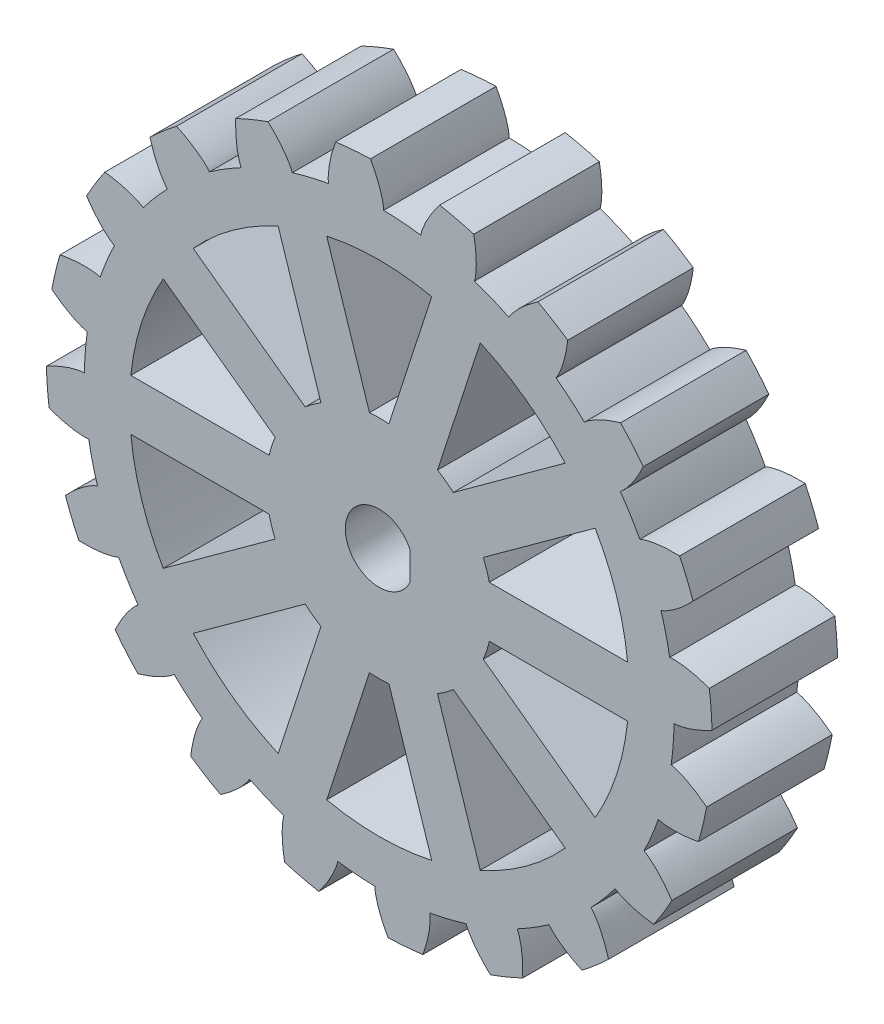
SolidWorks part; units mm, degrees
ref_plane "Front Plane" through (0, 0, 0) normal (0, 0, 1) x (1, 0, 0)
ref_plane "Top Plane" through (0, 0, 0) normal (0, 1, 0) x (1, 0, 0)
ref_plane "Right Plane" through (0, 0, 0) normal (1, 0, 0) x (0, 0, -1)
sketch "Sketch6" plane through (0, 0, 0) normal (0, 0, 1) x (1, 0, 0)
  line L0 (87.6899, 36.827) -> (87.6899, 90.4407) construction
  line L1 (87.6899, 61.8261) -> (62.7181, 61.8261) construction
  line L2 (87.6899, 61.8261) -> (56.3004, 50.4013) construction
  line L3 (79.6554, 58.9018) -> (87.6899, 61.8261) construction
  line L4 (77.8074, 58.1386) -> (87.3788, 62.5771) construction
  line L5 (76.0304, 57.2208) -> (86.9259, 63.45) construction
  line L6 (74.338, 56.1551) -> (86.3097, 64.4252) construction
  line L7 (81.5622, 59.5052) -> (87.8859, 61.2139) construction
  line L8 (83.5134, 59.9442) -> (87.9914, 60.7533) construction
  line L9 (85.4949, 60.2157) -> (88.0342, 60.454) construction
  line L10 (87.4923, 60.3177) -> (88.0428, 60.3223) construction
  line L11 (88.0428, 60.3223) -> (88.0425, 60.3158) construction
  line L12 (88.0425, 60.3158) -> (88.0425, 60.3094) construction
  line L13 (87.6899, 36.827) -> (85.2614, 67.5128) construction
  line L14 (111.173, 36.827) -> (112.6899, 36.827) construction
  line L15 (112.6899, 36.827) -> (114.2068, 36.827) construction
  circle A0 centre (87.6899, 36.827) radius 26.5169 construction
  circle A1 centre (87.6899, 36.827) radius 25 construction
  circle A2 centre (87.6899, 36.827) radius 23.4915 construction
  arc A3 (79.6554, 58.9018) -> (77.8074, 58.1386) centre (87.6899, 36.827) ccw construction
  arc A4 (77.8074, 58.1386) -> (76.0304, 57.2208) centre (87.6899, 36.827) ccw construction
  arc A5 (76.0304, 57.2208) -> (74.338, 56.1551) centre (87.6899, 36.827) ccw construction
  arc A6 (79.6554, 58.9018) -> (81.5622, 59.5052) centre (87.6899, 36.827) cw construction
  arc A7 (81.5622, 59.5052) -> (83.5134, 59.9442) centre (87.6899, 36.827) cw construction
  arc A8 (83.5134, 59.9442) -> (85.4949, 60.2157) centre (87.6899, 36.827) cw construction
  arc A9 (85.4949, 60.2157) -> (87.4923, 60.3177) centre (87.6899, 36.827) cw construction
  circle A10 centre (87.6899, 36.827) radius 23.485 construction
  spline S0 degree 3 poles (88.0425, 60.3094) (88.0393, 60.4586) (87.9965, 60.763) (87.8787, 61.2705) (87.6796, 61.8825) (87.2187, 62.9893) (86.7132, 63.8389) (86.3097, 64.4252) knots 0 0 0 0 0.099096 0.20382 0.346132 0.526411 1 1 1 1 construction
  spline S1 degree 3 poles (83.648, 59.9616) (83.6277, 60.1095) (83.6221, 60.4168) (83.6586, 60.9366) (83.759, 61.5723) (84.04, 62.7378) (84.4056, 63.6562) (84.7119, 64.2988) knots 0 0 0 0 0.099096 0.20382 0.346132 0.526411 1 1 1 1 construction
  point P7 (79.6554, 58.9018)
  dimension "D2" = 50
  dimension "D4" = 2
  dimension "D7" = 2
  dimension "D13" = 2
  dimension "D17" = 2
  dimension "D3" = 20
  dimension "D5" = 8.5502
  dimension "D6" = 10.5505
  dimension "D8" = 12.5505
  dimension "D9" = 2
  dimension "D10" = 14.5505
  dimension "D11" = 2
  dimension "D12" = 6.5505
  dimension "D14" = 4.5505
  dimension "D15" = 2
  dimension "D16" = 2.5505
  dimension "D18" = 0.5505
  dimension "D19" = 4.525
sketch "Sketch7" plane through (0, 0, 0) normal (0, 0, 1) x (1, 0, 0)
  circle A0 centre (87.6899, 36.827) radius 23.485 construction
  circle A1 centre (87.6899, 36.827) radius 26.5169 construction
  arc A2 (88.0425, 60.3094) -> (83.648, 59.9616) centre (87.6899, 36.827) ccw construction
  arc A3 (86.9912, 63.3347) -> (84.2104, 63.1146) centre (87.6899, 36.827) ccw construction
  spline S0 degree 3 poles (-1911.6865, 35.1483) (71.5756, 40.4372) (89.8382, 52.8293) (87.8787, 61.2705) (87.6796, 61.8825) (75.5402, 91.0375) (-65.3864, 59.6539) (2084.1552, 156.0334) knots -5.410264 -5.410264 -5.410264 -5.410264 0.099096 0.20382 0.346132 0.526411 21.176223 21.176223 21.176223 21.176223 only from (88.0425, 60.3094) to (86.3097, 64.4252) construction
  spline S1 degree 3 poles (2062.4411, 349.6638) (103.0357, 42.927) (83.0512, 52.2922) (83.6586, 60.9366) (83.759, 61.5723) (91.1612, 92.2738) (235.27, 83.4481) (-1902.673, -159.4872) knots -5.410264 -5.410264 -5.410264 -5.410264 0.099096 0.20382 0.346132 0.526411 21.176223 21.176223 21.176223 21.176223 only from (83.648, 59.9616) to (84.7119, 64.2988) construction
  spline S2 degree 3 poles (88.0425, 60.3094) (88.0393, 60.4586) (87.9965, 60.763) (87.8787, 61.2705) (87.6796, 61.8825) (87.3837, 62.5931) (87.1297, 63.087) (86.9912, 63.3347) knots 0 0 0 0 0.099096 0.20382 0.346132 0.526411 0.715001 0.715001 0.715001 0.715001 construction
  spline S3 degree 3 poles (83.648, 59.9616) (83.6277, 60.1095) (83.6221, 60.4168) (83.6586, 60.9366) (83.759, 61.5723) (83.9394, 62.3206) (84.1125, 62.8482) (84.2104, 63.1146) knots 0 0 0 0 0.099096 0.20382 0.346132 0.526411 0.715001 0.715001 0.715001 0.715001 construction
sketch "Sketch11" plane through (0, 0, 0) normal (0, 0, 1) x (1, 0, 0)
  circle A0 centre (0, 0) radius 23.485
  dimension "D1" = 46.97
extrude "Boss-Extrude6" add sketch "Sketch11" along normal blind 10
sketch "Sketch12" plane through (0, 0, 10) normal (0, 0, 1) x (1, 0, 0)
  arc A2 (-0.6987, 26.5077) -> (-3.4795, 26.2876) centre (0, 0) ccw
  arc A3 (0.3526, 23.4824) -> (-4.0419, 23.1346) centre (0, 0) ccw
  spline S2 degree 3 poles (-4.0419, 23.1346) (-4.0622, 23.2824) (-4.0678, 23.5897) (-4.0313, 24.1095) (-3.9309, 24.7452) (-3.7505, 25.4935) (-3.5774, 26.0212) (-3.4795, 26.2876) knots 0 0 0 0 0.099096 0.20382 0.346132 0.526411 0.715001 0.715001 0.715001 0.715001
  spline S3 degree 3 poles (0.3526, 23.4824) (0.3494, 23.6316) (0.3066, 23.9359) (0.1887, 24.4435) (-0.0104, 25.0555) (-0.3062, 25.7661) (-0.5602, 26.26) (-0.6987, 26.5077) knots 0 0 0 0 0.099096 0.20382 0.346132 0.526411 0.715001 0.715001 0.715001 0.715001
extrude "Boss-Extrude7" add sketch "Sketch12" against normal blind 10
pattern_circular "CirPattern2" count 20 over 360 of "Boss-Extrude7"
sketch "Sketch13" plane through (0, 0, 10) normal (0, 0, 1) x (1, 0, 0)
  line L0 (2.45, 1.1347) -> (2.45, -1.1347)
  arc A0 (2.45, 1.1347) -> (2.45, -1.1347) centre (0, 0) ccw
  dimension "D1" = 2.7
  dimension "D2" = 2.45
extrude "Cut-Extrude2" cut sketch "Sketch13" against normal blind 10
sketch "Sketch14" plane through (0, 0, 0) normal (0, 0, -1) x (-1, 0, 0)
  line L1 (-7.3601, 2.8365) -> (-17.1995, 9.9851)
  line L2 (-7.6217, -2.0314) -> (-19.7838, -2.0314)
  line L4 (-7.6217, 2.0314) -> (-19.7838, 2.0314)
  line L8 (-4.972, 6.1234) -> (-14.8114, 13.2721)
  line L9 (-4.2873, 6.6209) -> (-8.0455, 18.1877)
  line L10 (-0.4232, 7.8764) -> (-4.1815, 19.4432)
  line L11 (0.4232, 7.8764) -> (4.1815, 19.4432)
  line L12 (4.2873, 6.6209) -> (8.0455, 18.1877)
  line L13 (4.972, 6.1234) -> (14.8114, 13.2721)
  line L14 (7.3601, 2.8365) -> (17.1995, 9.9851)
  line L15 (7.6217, 2.0314) -> (19.7838, 2.0314)
  line L16 (7.6217, -2.0314) -> (19.7838, -2.0314)
  line L17 (7.3601, -2.8365) -> (17.1995, -9.9851)
  line L18 (4.972, -6.1234) -> (14.8114, -13.2721)
  line L19 (4.2873, -6.6209) -> (8.0455, -18.1877)
  line L20 (0.4232, -7.8764) -> (4.1815, -19.4432)
  line L21 (-0.4232, -7.8764) -> (-4.1815, -19.4432)
  line L22 (-4.2873, -6.6209) -> (-8.0455, -18.1877)
  line L23 (-4.972, -6.1234) -> (-14.8114, -13.2721)
  line L24 (-7.3601, -2.8365) -> (-17.1995, -9.9851)
  circle A0 centre (0, 0) radius 19.8878 construction
  arc A1 (-4.1815, -19.4432) -> (4.1815, -19.4432) centre (0, 0) ccw
  circle A2 centre (0, 0) radius 22.8878 construction
  arc A3 (-0.4232, -7.8764) -> (0.4232, -7.8764) centre (0, 0) ccw
  circle A4 centre (0, 0) radius 7.8878 construction
  arc A5 (-4.972, -6.1234) -> (-4.2873, -6.6209) centre (0, 0) ccw
  arc A6 (-14.8114, -13.2721) -> (-8.0455, -18.1877) centre (0, 0) ccw
  arc A7 (4.2873, -6.6209) -> (4.972, -6.1234) centre (0, 0) ccw
  arc A8 (8.0455, -18.1877) -> (14.8114, -13.2721) centre (0, 0) ccw
  arc A9 (17.1995, -9.9851) -> (19.7838, -2.0314) centre (0, 0) ccw
  arc A10 (7.3601, -2.8365) -> (7.6217, -2.0314) centre (0, 0) ccw
  arc A11 (7.6217, 2.0314) -> (7.3601, 2.8365) centre (0, 0) ccw
  arc A12 (19.7838, 2.0314) -> (17.1995, 9.9851) centre (0, 0) ccw
  arc A13 (4.972, 6.1234) -> (4.2873, 6.6209) centre (0, 0) ccw
  arc A14 (14.8114, 13.2721) -> (8.0455, 18.1877) centre (0, 0) ccw
  arc A15 (0.4232, 7.8764) -> (-0.4232, 7.8764) centre (0, 0) ccw
  arc A16 (4.1815, 19.4432) -> (-4.1815, 19.4432) centre (0, 0) ccw
  arc A17 (-4.2873, 6.6209) -> (-4.972, 6.1234) centre (0, 0) ccw
  arc A18 (-8.0455, 18.1877) -> (-14.8114, 13.2721) centre (0, 0) ccw
  arc A19 (-7.3601, 2.8365) -> (-7.6217, 2.0314) centre (0, 0) ccw
  arc A20 (-17.1995, 9.9851) -> (-19.7838, 2.0314) centre (0, 0) ccw
  arc A21 (-19.7838, -2.0314) -> (-17.1995, -9.9851) centre (0, 0) ccw
  arc A22 (-7.6217, -2.0314) -> (-7.3601, -2.8365) centre (0, 0) ccw
  point P8 (-13.8878, 0)
  point P56 (0, 0)
  dimension "D1" = 3
  dimension "D2" = 12
  dimension "D3" = 10
extrude "Cut-Extrude3" cut sketch "Sketch14" against normal through all
sketch "Sketch16" plane through (0, 0, 0) normal (0, 0, -1) x (-1, 0, 0)
  line L0 (-2.45, -1.1347) -> (-2.45, 1.1347) construction
  line L1 (-2.45, -1.1347) -> (-2.45, 1.1347)
  arc A0 (-2.45, -1.1347) -> (-2.45, 1.1347) centre (0, 0) ccw construction
  arc A1 (-2.45, -1.1347) -> (-2.45, 1.1347) centre (0, 0) ccw
  circle A2 centre (0, 0) radius 9
  dimension "D1" = 18
extrude "Boss-Extrude9" add sketch "Sketch16" along normal blind 10 and the other way up to surface
sketch "Sketch17" plane through (2.45, 0, 0) normal (-1, 0, 0) x (0, 0, 1)
  line L0 (-10, 1.1347) -> (-10, -1.1347) construction
  circle A0 centre (-5, 0) radius 1
  dimension "D1" = 2
  dimension "D2" = 5
extrude "Cut-Extrude4" cut sketch "Sketch17" against normal blind 20
